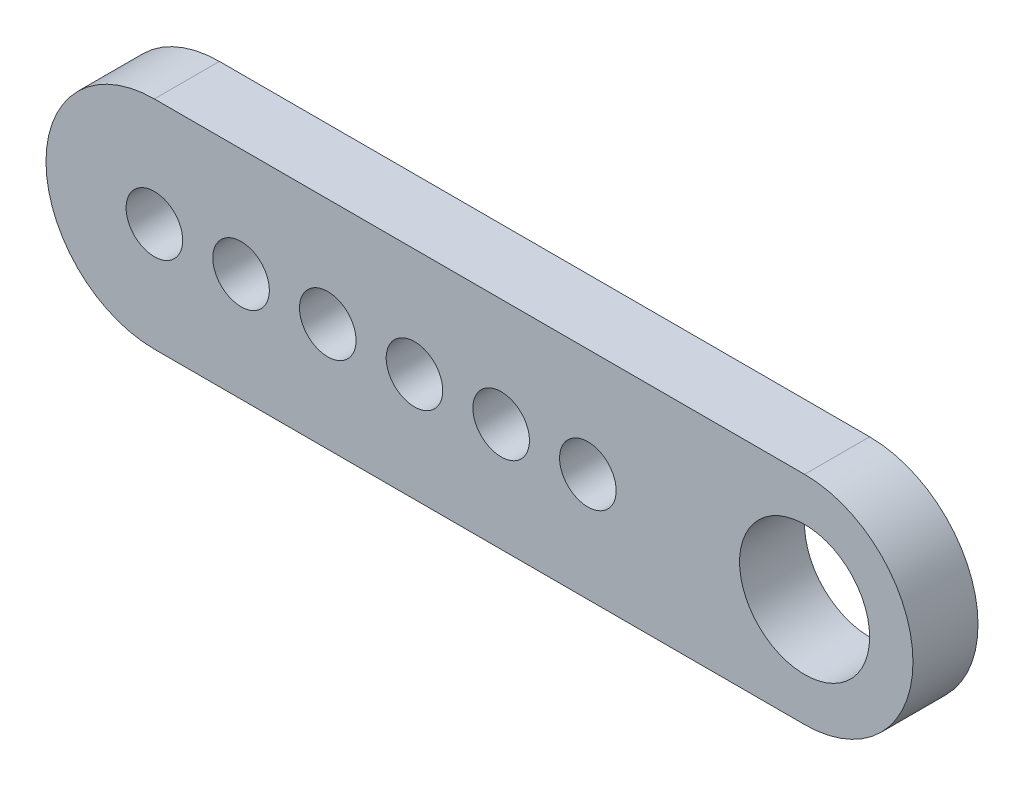
SolidWorks part; units mm, degrees
ref_plane "Plan de face" through (0, 0, 0) normal (0, 0, 1) x (1, 0, 0)
ref_plane "Plan de dessus" through (0, 0, 0) normal (0, 1, 0) x (1, 0, 0)
ref_plane "Plan de droite" through (0, 0, 0) normal (1, 0, 0) x (0, 0, -1)
sketch "Esquisse1" plane through (0, 0, 0) normal (0, 0, 1) x (1, 0, 0)
  line L0 (0, -5) -> (-30, -5)
  line L1 (0, 0) -> (-30, 0) construction
  line L2 (-30, 5) -> (0, 5)
  circle A0 centre (0, 0) radius 3
  circle A1 centre (0, 0) radius 5
  arc A2 (-30, 5) -> (-30, -5) centre (-30, 0) ccw
  circle A3 centre (-30, 0) radius 1.3051
  circle A4 centre (-26, 0) radius 1.3051
  circle A5 centre (-22, 0) radius 1.3051
  circle A6 centre (-18, 0) radius 1.3051
  circle A7 centre (-14, 0) radius 1.3051
  circle A8 centre (-10, 0) radius 1.3051
  dimension "D1" = 6
  dimension "D2" = 2
  dimension "D3" = 30
  dimension "D4" = 6
extrude "Boss.-Extru.1" add sketch "Esquisse1" along normal blind 3
